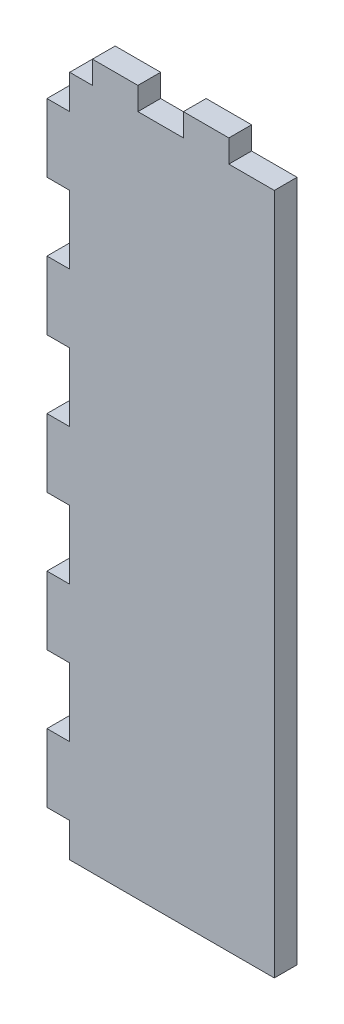
SolidWorks part; units mm, degrees
material "PVC 0.007 plastifié"
ref_plane "Plan de face" through (0, 0, 0) normal (0, 0, 1) x (1, 0, 0)
ref_plane "Plan de dessus" through (0, 0, 0) normal (0, 1, 0) x (1, 0, 0)
ref_plane "Plan de droite" through (0, 0, 0) normal (1, 0, 0) x (0, 0, -1)
sketch "Esquisse1" plane through (0, 0, 0) normal (0, 0, 1) x (1, 0, 0)
  line L1 (-57.84, 49.7727) -> (-7.84, 49.7727)
  line L2 (-57.84, 49.7727) -> (-57.84, -105.2273)
  line L3 (-57.84, -105.2273) -> (-7.84, -105.2273)
  line L4 (-7.84, 49.7727) -> (-7.84, -105.2273)
  dimension "D1" = 155
  dimension "D2" = 50
extrude "Boss.-Extru.1" add sketch "Esquisse1" along normal blind 5 contours L2 L3 L4 L1
sketch "Esquisse4" plane through (0, 0, 5) normal (0, 0, 1) x (1, 0, 0)
  line L0 (-57.84, 49.7727) -> (-7.84, 49.7727)
  line L1 (-57.84, 49.7727) -> (-57.84, -105.2273) construction
  line L2 (-7.84, 49.7727) -> (-7.84, -105.2273) construction
  line L3 (-57.84, 49.7727) -> (-7.84, 49.7727) construction
  line L4 (-57.84, -105.2273) -> (-7.84, -105.2273) construction
  line L5 (-57.84, 49.7727) -> (-52.84, 49.7727)
  line L6 (-57.84, 49.7727) -> (-57.84, 37.2727)
  line L7 (-57.84, 37.2727) -> (-52.84, 37.2727)
  line L8 (-47.84, 49.7727) -> (-47.84, 44.7727)
  line L9 (-57.84, 22.2727) -> (-52.84, 22.2727)
  line L10 (-57.84, 22.2727) -> (-57.84, 7.2727)
  line L11 (-57.84, 7.2727) -> (-52.84, 7.2727)
  line L12 (-52.84, 22.2727) -> (-52.84, 7.2727)
  line L13 (-57.84, -7.7273) -> (-52.84, -7.7273)
  line L14 (-57.84, -7.7273) -> (-57.84, -22.7273)
  line L15 (-57.84, -22.7273) -> (-52.84, -22.7273)
  line L16 (-52.84, -7.7273) -> (-52.84, -22.7273)
  line L17 (-57.84, -37.7273) -> (-52.84, -37.7273)
  line L18 (-57.84, -37.7273) -> (-57.84, -52.7273)
  line L19 (-57.84, -52.7273) -> (-52.84, -52.7273)
  line L20 (-52.84, -37.7273) -> (-52.84, -52.7273)
  line L21 (-57.84, -67.7273) -> (-52.84, -67.7273)
  line L22 (-57.84, -67.7273) -> (-57.84, -82.7273)
  line L23 (-57.84, -82.7273) -> (-52.84, -82.7273)
  line L24 (-52.84, -67.7273) -> (-52.84, -82.7273)
  line L25 (-57.84, -97.7273) -> (-52.84, -97.7273)
  line L26 (-57.84, -97.7273) -> (-57.84, -105.2273)
  line L27 (-57.84, -105.2273) -> (-52.84, -105.2273)
  line L28 (-52.84, -97.7273) -> (-52.84, -105.2273)
  line L29 (-47.84, 44.7727) -> (-52.84, 44.7727)
  line L30 (-37.84, 49.7727) -> (-27.84, 49.7727)
  line L31 (-37.84, 49.7727) -> (-37.84, 44.7727)
  line L32 (-37.84, 44.7727) -> (-27.84, 44.7727)
  line L33 (-27.84, 49.7727) -> (-27.84, 44.7727)
  line L34 (-7.84, 49.7727) -> (-17.84, 49.7727)
  line L35 (-7.84, 49.7727) -> (-7.84, 44.7727)
  line L36 (-7.84, 44.7727) -> (-17.84, 44.7727)
  line L37 (-17.84, 49.7727) -> (-17.84, 44.7727)
  line L38 (-52.84, 44.7727) -> (-52.84, 37.2727)
  line L39 (-52.84, 37.2727) -> (2.4728, 63.9644)
  dimension "D1" = 0
  dimension "D2" = 12.5
  dimension "D3" = 5
  dimension "D4" = 15
  dimension "D5" = 5
  dimension "D6" = 15
  dimension "D7" = 15
  dimension "D8" = 5
  dimension "D9" = 15
  dimension "D10" = 15
  dimension "D11" = 15
  dimension "D12" = 5
  dimension "D13" = 15
  dimension "D14" = 15
  dimension "D15" = 5
  dimension "D16" = 7.5
  dimension "D17" = 5
  dimension "D18" = 10
  dimension "D19" = 5
  dimension "D20" = 20
  dimension "D21" = 10
  dimension "D22" = 10
  dimension "D23" = 5
extrude "Enlèv. mat.-Extru.4" cut sketch "Esquisse4" against normal blind 5 contours L35 L36 L37 L34 | L13 L16 L15 L14 | L9 L12 L11 L10 | L25 L28 L27 L26 | L24 L23 L22 L21 | L17 L20 L19 L18 | L32 L33 L30 L31 | L8 L29 L38 L7 L6 L0
sketch "Esquisse7" plane through (0, 0, 5) normal (0, 0, 1) x (1, 0, 0)
  line L1 (-57.84, 49.7727) -> (-47.84, 49.7727)
  line L2 (-57.84, 49.7727) -> (-57.84, 44.7727)
  line L3 (-57.84, 44.7727) -> (-47.84, 44.7727)
  line L4 (-47.84, 49.7727) -> (-47.84, 44.7727)
  dimension "D1" = 10
  dimension "D2" = 5
extrude "Enlèv. mat.-Extru.5" cut sketch "Esquisse7" against normal blind 5
sketch "Esquisse8" plane through (0, 0, 5) normal (0, 0, 1) x (1, 0, 0)
  line L1 (-57.84, 44.7727) -> (-52.84, 44.7727)
  line L2 (-57.84, 44.7727) -> (-57.84, 37.2727)
  line L3 (-57.84, 37.2727) -> (-52.84, 37.2727)
  line L4 (-52.84, 44.7727) -> (-52.84, 37.2727)
  dimension "D1" = 7.5
  dimension "D2" = 5
extrude "Enlèv. mat.-Extru.6" cut sketch "Esquisse8" against normal blind 5 contours L3 L4 L1 L2
